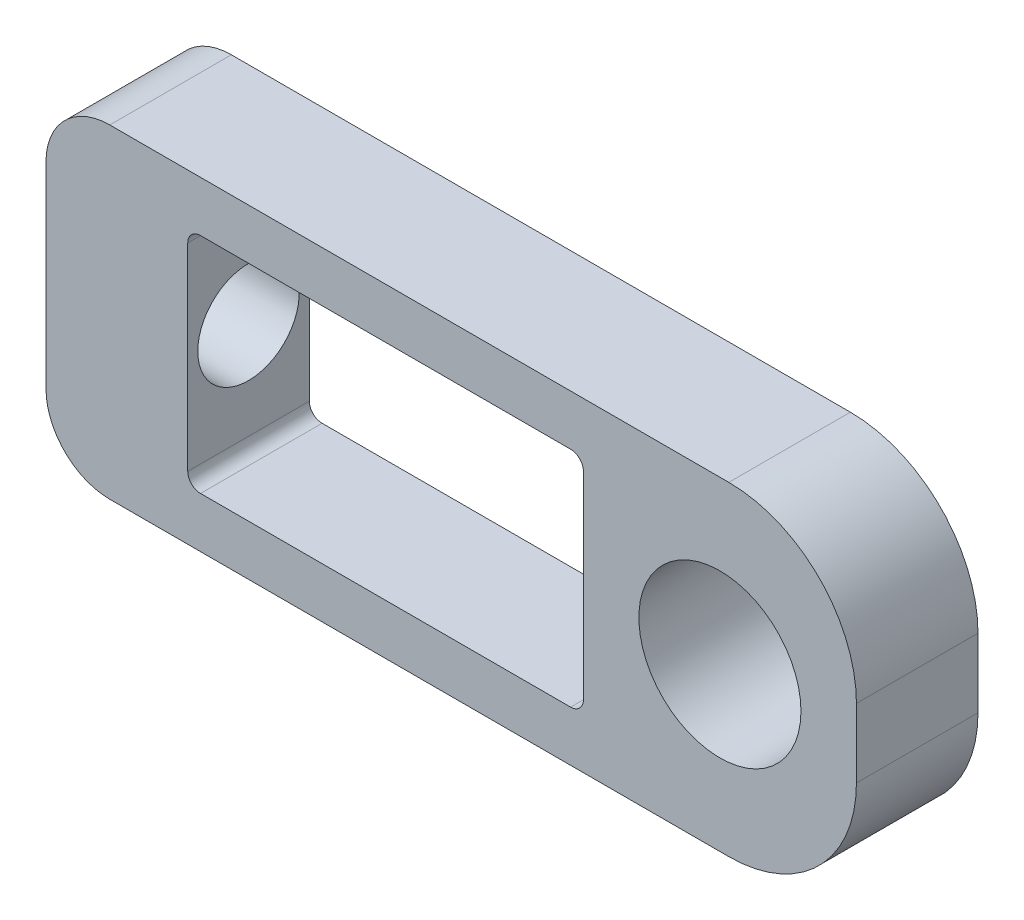
SolidWorks part; units mm, degrees
ref_plane "Front Plane" through (0, 0, 0) normal (0, 0, 1) x (1, 0, 0)
ref_plane "Top Plane" through (0, 0, 0) normal (0, 1, 0) x (1, 0, 0)
ref_plane "Right Plane" through (0, 0, 0) normal (1, 0, 0) x (0, 0, -1)
sketch "Sketch1" plane through (0, 0, 0) normal (0, 0, 1) x (1, 0, 0)
  line L1 (0, 0) -> (63.5, 0)
  line L2 (0, 0) -> (0, 25.4)
  line L3 (0, 25.4) -> (63.5, 25.4)
  line L4 (63.5, 0) -> (63.5, 25.4)
  dimension "D1" = 63.5
  dimension "D2" = 25.4
extrude "Boss-Extrude1" add sketch "Sketch1" along normal blind 9.525
sketch "Sketch5" plane through (0, 0, 9.525) normal (0, 0, 1) x (1, 0, 0)
  line L0 (42.1062, 12.7) -> (63.5, 12.7) construction
  line L1 (63.5, 0) -> (63.5, 25.4) construction
  line L6 (11.1062, 3.95) -> (42.1062, 3.95)
  line L7 (11.1062, 3.95) -> (11.1062, 21.45)
  line L8 (11.1062, 21.45) -> (42.1062, 21.45)
  line L9 (42.1062, 3.95) -> (42.1062, 21.45)
  line L10 (11.1062, 3.95) -> (42.1062, 21.45) construction
  line L11 (11.1062, 21.45) -> (42.1062, 3.95) construction
  circle A1 centre (52.8031, 12.7) radius 6.35
  point P11 (26.6062, 12.7)
  dimension "D1" = 12.7
  dimension "D2" = 31
  dimension "D3" = 17.5
extrude "Cut-Extrude3" cut sketch "Sketch5" against normal through all
sketch "Sketch4" plane through (0, 0, 0) normal (-1, 0, 0) x (0, 0, 1)
  line L0 (0, 25.4) -> (9.525, 0) construction
  circle A1 centre (4.7625, 12.7) radius 3.9751
  dimension "D1" = 7.9502
extrude "Cut-Extrude2" cut sketch "Sketch4" against normal up to next
fillet "Fillet4" radius 10 2 edges at (63.5, 0, 4.7625) (63.5, 25.4, 4.7625)
fillet "Fillet5" radius 5 2 edges at (0, 0, 4.7625) (0, 25.4, 4.7625)
fillet "Fillet6" radius 1 4 edges at (11.1062, 21.45, 4.7625) (11.1062, 3.95, 4.7625) (42.1062, 3.95, 4.7625) (42.1062, 21.45, 4.7625)
